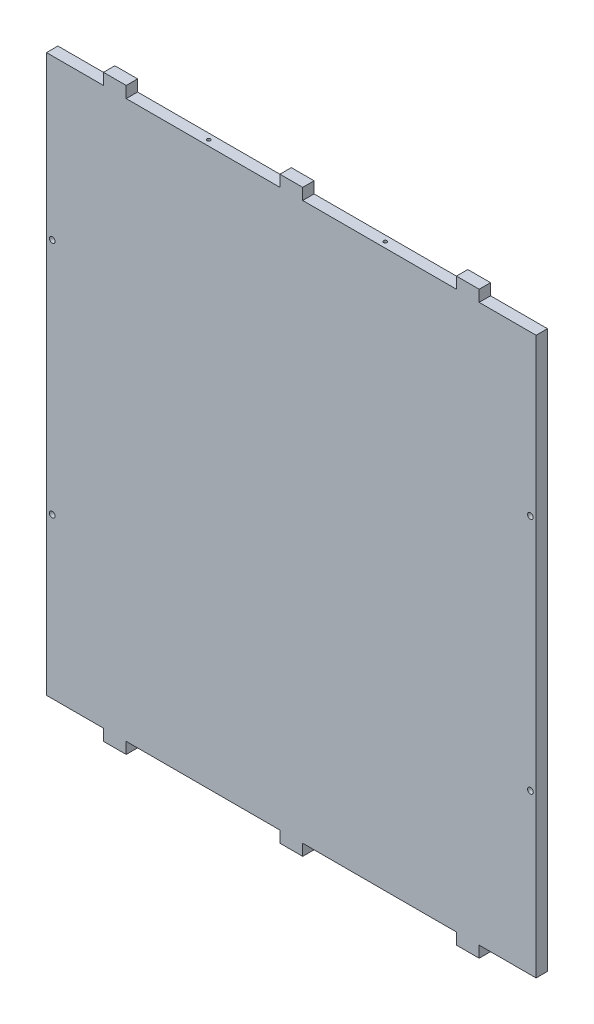
SolidWorks part; units mm, degrees
ref_plane "Ebene vorne" through (0, 0, 0) normal (0, 0, 1) x (1, 0, 0)
ref_plane "Ebene oben" through (0, 0, 0) normal (0, 1, 0) x (1, 0, 0)
ref_plane "Ebene rechts" through (0, 0, 0) normal (1, 0, 0) x (0, 0, -1)
sketch "Skizze1" plane through (0, 0, 0) normal (0, 0, 1) x (1, 0, 0)
  line L0 (0, 0) -> (0, -83406.5938) construction
  line L1 (0, 0) -> (83406.5938, 0) construction
  line L2 (55, 67.225) -> (75, 67.225)
  line L3 (-100, -67.225) -> (100, -67.225)
  line L4 (10.5, -37.555) -> (10.5, -42.555)
  line L5 (-100, 67.225) -> (-85, 67.225)
  line L6 (50.5, -37.555) -> (55.5, -37.555)
  line L7 (-100, -67.225) -> (100, 67.225) construction
  line L8 (-100, 67.225) -> (100, -67.225) construction
  line L9 (100, 47.225) -> (100, 67.225)
  line L10 (75, 67.225) -> (75, 72.225)
  line L11 (75, 72.225) -> (85, 72.225)
  line L12 (85, 67.225) -> (85, 72.225)
  line L13 (85, 67.225) -> (100, 67.225)
  line L14 (45, 67.225) -> (45, 72.225)
  line L15 (45, 72.225) -> (55, 72.225)
  line L16 (55, 67.225) -> (55, 72.225)
  line L17 (50.5, -37.555) -> (50.5, -42.555)
  line L18 (50.5, -42.555) -> (55.5, -42.555)
  line L19 (55.5, -37.555) -> (55.5, -42.555)
  line L20 (15.5, -42.555) -> (10.5, -42.555)
  line L21 (100, 47.225) -> (105, 47.225)
  line L22 (15.5, -37.555) -> (15.5, -42.555)
  line L23 (100, 37.225) -> (105, 37.225)
  line L24 (105, 47.225) -> (105, 37.225)
  line L25 (15.5, -37.555) -> (10.5, -37.555)
  line L26 (-75, 67.225) -> (45, 67.225)
  line L27 (100, -47.225) -> (100, -67.225)
  line L29 (-75, 67.225) -> (-75, 72.225)
  line L30 (-75, 72.225) -> (-85, 72.225)
  line L31 (105, -47.225) -> (105, -37.225)
  line L32 (100, -37.225) -> (105, -37.225)
  line L33 (-85, 67.225) -> (-85, 72.225)
  line L34 (100, -47.225) -> (105, -47.225)
  line L38 (100, 37.225) -> (100, -37.225)
  line L44 (-100, 37.225) -> (-100, -37.225)
  line L48 (-100, -47.225) -> (-105, -47.225)
  line L50 (-100, -37.225) -> (-105, -37.225)
  line L51 (-105, -47.225) -> (-105, -37.225)
  line L53 (-100, -47.225) -> (-100, -67.225)
  line L55 (-105, 47.225) -> (-105, 37.225)
  line L56 (-100, 37.225) -> (-105, 37.225)
  line L58 (-100, 47.225) -> (-105, 47.225)
  line L62 (-100, 47.225) -> (-100, 67.225)
  line L63 (33, -37.555) -> (33, -42.555) construction
  line L64 (25.5, -37.555) -> (40.5, -37.555)
  line L65 (25.5, -37.555) -> (25.5, -42.555)
  line L66 (25.5, -42.555) -> (40.5, -42.555)
  line L67 (40.5, -37.555) -> (40.5, -42.555)
  line L68 (105, 0) -> (105, -50000) construction
  point P5 (0, 0)
  dimension "D1" = 134.45
  dimension "D2" = 200
  dimension "D3" = 10
  dimension "D4" = 20
  dimension "D5" = 5
  dimension "D6" = 20
  dimension "D7" = 20
  dimension "D8" = 29.67
  dimension "D9" = 72
  dimension "D10" = 15
  dimension "D11" = 105
  dimension "D12" = 10
  dimension "D13" = 5
  dimension "D14" = 15
extrude "Aufsatz-Linear austragen1" add sketch "Skizze1" along normal blind 5
sketch "Skizze2" plane through (0, 0, 5) normal (0, 0, 1) x (1, 0, 0)
  line L0 (-42, 48.7841) -> (-42, -49951.2159) construction
  line L1 (-80.5107, -3.925) -> (49919.4893, -3.925) construction
  line L2 (-100, 67.225) -> (-85, 67.225) construction
  line L4 (100, 37.225) -> (100, -37.225) construction
  circle A0 centre (-59.5, 4.075) radius 2.75
  circle A1 centre (-24.5, 4.075) radius 2.75 construction
  circle A2 centre (-59.5, -11.925) radius 2.75 construction
  circle A3 centre (-24.5, -11.925) radius 2.75
  dimension "D1" = 5.5
  dimension "D2" = 63.15
  dimension "D3" = 142
  dimension "D4" = 35
  dimension "D5" = 16
extrude "Schnitt-Linear austragen1" cut sketch "Skizze2" against normal through all
sketch "Skizze3" plane through (0, 0, 5) normal (0, 0, 1) x (1, 0, 0)
  line L0 (33, -42.555) -> (33, -17.555) construction
  line L1 (25, -17.555) -> (41, -17.555)
  line L2 (23, -19.555) -> (23, -35.555)
  line L3 (37, -37.555) -> (41, -37.555)
  line L4 (43, -19.555) -> (43, -35.555)
  line L5 (-14.5, -32.225) -> (4.5, -32.225) construction
  line L6 (-17.5, -35.225) -> (-17.5, -54.225) construction
  line L7 (-14.5, -57.225) -> (4.5, -57.225) construction
  line L8 (7.5, -35.225) -> (7.5, -54.225) construction
  line L9 (25.5, -42.555) -> (40.5, -42.555) construction
  line L10 (25.5, -37.555) -> (40.5, -37.555) construction
  line L11 (29, -37.555) -> (25, -37.555)
  line L12 (-66.5, 54.225) -> (-66.5, 35.225)
  line L13 (37, -37.555) -> (29, -37.555)
  line L14 (-5, -32.225) -> (-5, -50032.225) construction
  line L17 (-88.5, 32.225) -> (-69.5, 32.225)
  line L18 (-100, -67.225) -> (100, -67.225) construction
  line L19 (-5, 57.225) -> (49995, 57.225) construction
  line L20 (-100, 67.225) -> (-85, 67.225) construction
  line L21 (-42, 57.225) -> (-42, -49942.775) construction
  line L24 (4.5, 57.225) -> (-14.5, 57.225)
  line L25 (7.5, 54.225) -> (7.5, 35.225)
  line L26 (4.5, 32.225) -> (-14.5, 32.225)
  line L27 (-17.5, 54.225) -> (-17.5, 35.225)
  line L28 (-91.5, 54.225) -> (-91.5, 35.225)
  line L29 (-88.5, 57.225) -> (-69.5, 57.225)
  line L30 (-79, 57.225) -> (-79, -49942.775) construction
  line L31 (-5, 22.3625) -> (49995, 22.3625) construction
  line L32 (4.5, -12.5) -> (-14.5, -12.5) construction
  line L33 (-17.5, -9.5) -> (-17.5, 9.5) construction
  line L34 (4.5, 12.5) -> (-14.5, 12.5) construction
  line L35 (7.5, -9.5) -> (7.5, 9.5) construction
  line L36 (4.5, 32.225) -> (4.5, 12.5) construction
  line L37 (4.5, -12.5) -> (4.5, -32.225) construction
  line L38 (4.5, -32.225) -> (4.5, -12.5) construction
  circle A0 centre (-24.5, -11.925) radius 2.75 construction
  arc A1 (23, -35.555) -> (25, -37.555) centre (25, -35.555) ccw
  arc A2 (43, -35.555) -> (41, -37.555) centre (41, -35.555) cw
  arc A3 (43, -19.555) -> (41, -17.555) centre (41, -19.555) ccw
  arc A4 (25, -17.555) -> (23, -19.555) centre (25, -19.555) ccw
  arc A5 (-17.5, -54.225) -> (-14.5, -57.225) centre (-14.5, -54.225) ccw construction
  arc A6 (7.5, -54.225) -> (4.5, -57.225) centre (4.5, -54.225) cw construction
  arc A8 (7.5, -35.225) -> (4.5, -32.225) centre (4.5, -35.225) ccw construction
  arc A9 (-14.5, -32.225) -> (-17.5, -35.225) centre (-14.5, -35.225) ccw construction
  arc A10 (7.5, 35.225) -> (4.5, 32.225) centre (4.5, 35.225) cw
  arc A11 (-14.5, 32.225) -> (-17.5, 35.225) centre (-14.5, 35.225) cw
  arc A12 (-17.5, 54.225) -> (-14.5, 57.225) centre (-14.5, 54.225) cw
  arc A14 (4.5, 57.225) -> (7.5, 54.225) centre (4.5, 54.225) cw
  arc A15 (-88.5, 57.225) -> (-91.5, 54.225) centre (-88.5, 54.225) ccw
  arc A16 (-66.5, 54.225) -> (-69.5, 57.225) centre (-69.5, 54.225) ccw
  arc A17 (-69.5, 32.225) -> (-66.5, 35.225) centre (-69.5, 35.225) ccw
  arc A18 (-91.5, 35.225) -> (-88.5, 32.225) centre (-88.5, 35.225) ccw
  circle A19 centre (-59.5, 4.075) radius 2.75 construction
  arc A20 (-17.5, -9.5) -> (-14.5, -12.5) centre (-14.5, -9.5) ccw construction
  arc A21 (-14.5, 12.5) -> (-17.5, 9.5) centre (-14.5, 9.5) ccw construction
  arc A22 (7.5, 9.5) -> (4.5, 12.5) centre (4.5, 9.5) ccw construction
  arc A23 (4.5, -12.5) -> (7.5, -9.5) centre (4.5, -9.5) ccw construction
  point P19 (23, -37.555)
  point P22 (43, -37.555)
  point P25 (43, -17.555)
  point P28 (23, -17.555)
  point P52 (43, -37.555)
  point P53 (-5, -32.225)
  point P67 (-17.5, 32.225)
  point P70 (-17.5, 57.225)
  point P73 (7.5, 57.225)
  point P86 (-91.5, 57.225)
  point P87 (-66.5, 57.225)
  point P88 (-66.5, 32.225)
  point P91 (-79, 57.225)
  dimension "D1" = 20
  dimension "D2" = 20
  dimension "D6" = 25
  dimension "D3" = 2
  dimension "D7" = 3
  dimension "D12" = 25
  dimension "D5" = 19.5
  dimension "D15" = 2
  dimension "D17" = 3
  dimension "D18" = 19.5
  dimension "D4" = 10
  dimension "D8" = 25
  dimension "D9" = 25
  dimension "D11" = 10
  dimension "D13" = 0
  dimension "D14" = 8
extrude "Schnitt-Linear austragen2" cut sketch "Skizze3" against normal through all
sketch "Skizze4" plane through (0, 0, 5) normal (0, 0, 1) x (1, 0, 0)
  line L0 (55, 67.225) -> (75, 67.225) construction
  line L1 (100, 47.225) -> (100, 67.225) construction
  line L2 (-100, -67.225) -> (100, -67.225) construction
  line L3 (-80.5, -30.925) -> (49919.5, -30.925) construction
  line L4 (-80.5, -30.925) -> (-80.5, -50030.925) construction
  circle A0 centre (45.5, 53.325) radius 7.5 construction
  circle A1 centre (-80.5, -30.925) radius 7.5
  circle A2 centre (-59.5, 4.075) radius 2.75 construction
  circle A3 centre (-80.5, -11.925) radius 7.5
  circle A4 centre (-80.5, -49.925) radius 7.5
  dimension "D1" = 13.9
  dimension "D3" = 15
  dimension "D5" = 21
  dimension "D6" = 19
  dimension "D2" = 54.5
  dimension "D4" = 36.3
extrude "Schnitt-Linear austragen3" cut sketch "Skizze4" against normal through all
sketch "Skizze5" plane through (0, 0, 5) normal (0, 0, 1) x (1, 0, 0)
  line L0 (-8, -45.225) -> (-8, -3.225) construction
  line L1 (83, -12.225) -> (-8, -12.225) construction
  line L2 (-100, -67.225) -> (100, -67.225) construction
  line L3 (100, 37.225) -> (100, -37.225) construction
  line L4 (-30.2483, -49.225) -> (49969.7517, -49.225) construction
  line L5 (-17.9531, -56.225) -> (49982.0469, -56.225) construction
  line L6 (22.5, -56.9878) -> (22.5, -50056.9878) construction
  line L7 (37.5, -10.225) -> (37.5, -50010.225) construction
  circle A0 centre (-8, -45.225) radius 0.75
  circle A1 centre (-8, -3.225) radius 0.75
  circle A2 centre (83, -12.225) radius 0.75
  circle A3 centre (-15, -56.225) radius 6
  circle A4 centre (0, -56.225) radius 6
  circle A5 centre (15, -56.225) radius 6
  circle A6 centre (30, -56.225) radius 6
  circle A7 centre (45, -56.225) radius 6
  circle A8 centre (60, -56.225) radius 6
  circle A9 centre (75, -56.225) radius 6
  circle A10 centre (90, -56.225) radius 6
  point P36 (37.5, -12.225)
  dimension "D1" = 1.5
  dimension "D9" = 12
  dimension "D2" = 42
  dimension "D4" = 91
  dimension "D3" = 9
  dimension "D5" = 22
  dimension "D6" = 17
  dimension "D7" = 4
  dimension "D10" = 7
  dimension "D11" = 15
  dimension "D8" = 8
extrude "Sensors" cut sketch "Skizze5" against normal through all
sketch "Skizze6" plane through (0, 0, 0) normal (0, 0, -1) x (-1, 0, 0)
  line L0 (100, -67.225) -> (-100, -67.225) construction
  line L1 (160, 47.225) -> (160, 37.225)
  line L2 (100, 67.225) -> (100, -67.225)
  line L3 (100, -67.225) -> (160, -67.225)
  line L4 (160, 67.225) -> (160, 47.225)
  line L6 (100, -37.225) -> (105, -37.225) construction
  line L7 (160, -47.225) -> (160, -67.225)
  line L8 (100, -47.225) -> (105, -47.225) construction
  line L9 (100, 47.225) -> (105, 47.225) construction
  line L10 (100, 37.225) -> (105, 37.225) construction
  line L11 (75, 67.225) -> (-45, 67.225) construction
  line L17 (160, 37.225) -> (160, -37.225)
  line L18 (-30.5, 67.225) -> (100, 67.225)
  line L19 (-30.5, 67.225) -> (-30.5, 177.225)
  line L20 (-30.5, 177.225) -> (160, 177.225)
  line L21 (160, 67.225) -> (160, 177.225)
  line L22 (-100, 47.225) -> (-100, 67.225) construction
  line L23 (160, -37.225) -> (160, -47.225)
  dimension "D1" = 60
  dimension "D2" = 110
  dimension "D3" = 69.5
extrude "Aufsatz-Linear austragen2" add sketch "Skizze6" against normal blind 5
sketch "Skizze7" plane through (0, 0, 0) normal (0, 0, -1) x (-1, 0, 0)
  line L0 (71.5, 32.775) -> (96.5, 32.775) construction
  line L1 (160, -67.225) -> (-100, -67.225) construction
  line L4 (91.5, 54.225) -> (91.5, 35.225) construction
  line L5 (46.5, 32.775) -> (71.5, 32.775) construction
  line L6 (122.7956, 60.525) -> (50122.7956, 60.525) construction
  circle A0 centre (71.5, 32.775) radius 1.25
  circle A1 centre (96.5, 32.775) radius 1.25
  circle A4 centre (46.5, 32.775) radius 1.25
  dimension "D3" = 2.5
  dimension "D1" = 100
  dimension "D2" = 25
  dimension "D4" = 20
extrude "Schnitt-Linear austragen5" cut sketch "Skizze7" against normal through all
sketch "Sketch1" plane through (0, 0, 5) normal (0, 0, 1) x (1, 0, 0)
  line L1 (30.5, 177.225) -> (100, 177.225)
  line L2 (30.5, 177.225) -> (30.5, 67.225)
  line L3 (30.5, 67.225) -> (100, 67.225)
  line L4 (100, 177.225) -> (100, 67.225)
extrude "Boss-Extrude1" add sketch "Sketch1" against normal blind 5
sketch "Skizze9" plane through (0, 0, 5) normal (0, 0, 1) x (1, 0, 0)
  line L0 (-33.1526, 41.015) -> (49966.8474, 41.015) construction
  line L1 (38.5, 36.3664) -> (38.5, 48631.464) construction
  line L5 (-2, 7.1234) -> (-2, 89.5656) construction
  line L7 (-17.5, 54.225) -> (-17.5, 35.225) construction
  line L8 (4.5, 57.225) -> (-14.5, 57.225) construction
  circle A0 centre (8, 71.515) radius 0.75
  circle A1 centre (69, 71.515) radius 0.75
  circle A2 centre (8, 10.515) radius 0.75
  circle A3 centre (69, 10.515) radius 0.75
  circle A4 centre (-2, 5.015) radius 6
  circle A5 centre (-2, 29.015) radius 6
  circle A6 centre (-2, 53.015) radius 6
  circle A7 centre (-2, 77.015) radius 6
  dimension "D1" = 1.5
  dimension "D8" = 12
  dimension "D2" = 61
  dimension "D3" = 61
  dimension "D7" = 24
  dimension "D5" = 15.5
  dimension "D9" = 4.21
  dimension "D4" = 10
  dimension "D6" = 4
extrude "DiscreteChannel" cut sketch "Skizze9" against normal through all
sketch "Skizze10" plane through (0, 0, 5) normal (0, 0, 1) x (1, 0, 0)
  line L0 (-50, 127.2474) -> (-50, -49872.7526) construction
  line L1 (-69.94, 115.225) -> (49930.06, 115.225) construction
  line L4 (-50.8687, 166.225) -> (49949.1313, 166.225) construction
  line L5 (-75.5, 136.225) -> (49924.5, 136.225) construction
  line L6 (-72.5, 172.225) -> (-27.5, 172.225) construction
  line L7 (-72.5, 166.225) -> (-72.5, 151.225) construction
  line L8 (-160, 177.225) -> (100, 177.225) construction
  line L9 (100, 47.225) -> (100, 177.225) construction
  circle A0 centre (-4, 136.225) radius 0.75
  circle A1 centre (-4, 94.225) radius 0.75
  circle A2 centre (-96, 136.225) radius 0.75
  circle A3 centre (-96, 94.225) radius 0.75
  circle A4 centre (-72.5, 166.225) radius 6
  circle A5 centre (-2, 5.015) radius 6 construction
  circle A6 centre (-57.5, 166.225) radius 6
  circle A7 centre (-42.5, 166.225) radius 6
  circle A8 centre (-27.5, 166.225) radius 6
  circle A9 centre (-27.5, 151.225) radius 6
  circle A10 centre (-42.5, 151.225) radius 6
  circle A11 centre (-57.5, 151.225) radius 6
  circle A12 centre (-72.5, 151.225) radius 6
  point P20 (-50, 172.225)
  dimension "D6" = 4
  dimension "D5" = 1.5
  dimension "D1" = 42
  dimension "D2" = 92
  dimension "D7" = 15
  dimension "D9" = 30
  dimension "D8" = 15
  dimension "D4" = 11
  dimension "D10" = 150
  dimension "D3" = 2
extrude "ContChannel" cut sketch "Skizze10" against normal through all
sketch "Sketch2" plane through (0, 0, 5) normal (0, 0, 1) x (1, 0, 0)
  line L0 (-14.5, 32.225) -> (-7.0691, 32.225) construction
  line L1 (3.0691, 32.225) -> (4.5, 32.225) construction
  line L2 (7.5, 35.225) -> (7.5, 54.225) construction
  line L3 (4.5, 57.225) -> (2.275, 57.225) construction
  line L4 (-6.275, 57.225) -> (-14.5, 57.225) construction
  line L5 (-17.5, 54.225) -> (-17.5, 35.225) construction
  line L6 (-14.5, 32.225) -> (-7.0691, 32.225)
  line L7 (3.0691, 32.225) -> (4.5, 32.225)
  line L8 (7.5, 35.225) -> (7.5, 54.225)
  line L9 (4.5, 57.225) -> (2.275, 57.225)
  line L10 (-6.275, 57.225) -> (-14.5, 57.225)
  line L11 (-17.5, 54.225) -> (-17.5, 35.225)
  arc A0 (-17.5, 35.225) -> (-14.5, 32.225) centre (-14.5, 35.225) ccw construction
  arc A1 (-7.0691, 32.225) -> (3.0691, 32.225) centre (-2, 29.015) ccw construction
  arc A2 (4.5, 32.225) -> (7.5, 35.225) centre (4.5, 35.225) ccw construction
  arc A3 (7.5, 54.225) -> (4.5, 57.225) centre (4.5, 54.225) ccw construction
  arc A4 (2.275, 57.225) -> (-6.275, 57.225) centre (-2, 53.015) ccw construction
  arc A5 (-14.5, 57.225) -> (-17.5, 54.225) centre (-14.5, 54.225) ccw construction
  arc A6 (-17.5, 35.225) -> (-14.5, 32.225) centre (-14.5, 35.225) ccw
  arc A7 (-7.0691, 32.225) -> (3.0691, 32.225) centre (-2, 29.015) ccw construction
  arc A8 (4.5, 32.225) -> (7.5, 35.225) centre (4.5, 35.225) ccw
  arc A9 (7.5, 54.225) -> (4.5, 57.225) centre (4.5, 54.225) ccw
  arc A10 (2.275, 57.225) -> (-6.275, 57.225) centre (-2, 53.015) ccw construction
  arc A11 (-14.5, 57.225) -> (-17.5, 54.225) centre (-14.5, 54.225) ccw
  arc A12 (-7.0691, 32.225) -> (3.0691, 32.225) centre (-2, 29.015) cw
  arc A13 (-6.275, 57.225) -> (2.275, 57.225) centre (-2, 53.015) ccw
extrude "Boss-Extrude2" add sketch "Sketch2" against normal blind 5
sketch "Skizze8" plane through (0, 0, 5) normal (0, 0, 1) x (1, 0, 0)
  line L0 (-165.5788, 126.725) -> (49834.4212, 126.725) construction
  line L1 (78, 176.1292) -> (78, 50176.1292) construction
  line L2 (-160, 177.225) -> (100, 177.225) construction
  line L3 (100, 47.225) -> (100, 177.225) construction
  line L5 (62.5, 100.225) -> (93.5, 100.225) construction
  circle A0 centre (62.5, 153.225) radius 0.75
  circle A1 centre (93.5, 153.225) radius 0.75
  circle A2 centre (62.5, 100.225) radius 0.75
  circle A3 centre (93.5, 100.225) radius 0.75
  circle A4 centre (78, 86.225) radius 7.5
  circle A5 centre (-80.5, -11.925) radius 7.5 construction
  circle A6 centre (78, 167.225) radius 7.5
  dimension "D1" = 1.5
  dimension "D2" = 53
  dimension "D3" = 31
  dimension "D4" = 14
  dimension "D5" = 10
  dimension "D6" = 6.5
extrude "StepDownConverter" cut sketch "Skizze8" against normal through all
sketch "Sketch3" plane through (0, 0, 5) normal (0, 0, 1) x (1, 0, 0)
  line L0 (46.6666, 126.725) -> (50046.6666, 126.725) construction
  line L1 (100, 47.225) -> (100, 177.225) construction
  line L2 (93.5, 153.225) -> (93.5, 100.225) construction
  line L3 (78, 167.225) -> (50078, 167.225) construction
  circle A0 centre (21.85, 147.68) radius 0.75
  circle A1 centre (87.89, 102.59) radius 0.75
  circle A2 centre (87.89, 150.86) radius 0.75
  circle A3 centre (21.85, 105.77) radius 0.75
  circle A4 centre (13, 167.225) radius 5
  circle A5 centre (28, 167.225) radius 5
  circle A6 centre (43, 167.225) radius 5
  circle A7 centre (58, 167.225) radius 5
  circle A8 centre (78, 167.225) radius 7.5 construction
  circle A9 centre (13, 86.225) radius 5
  point P10 (93.5, 126.725)
  dimension "D4" = 1.5
  dimension "D6" = 10
  dimension "D1" = 66.04
  dimension "D2" = 41.91
  dimension "D3" = 3.18
  dimension "D5" = 12.11
  dimension "D8" = 15
  dimension "D9" = 20
  dimension "D7" = 4
extrude "BBB" cut sketch "Sketch3" against normal blind 5
sketch "Sketch4" plane through (0, 0, 5) normal (0, 0, 1) x (1, 0, 0)
  line L0 (-88.5, 32.225) -> (-72.6225, 32.225) construction
  line L1 (-70.3775, 32.225) -> (-69.5, 32.225) construction
  line L2 (-66.5, 35.225) -> (-66.5, 54.225) construction
  line L3 (-69.5, 57.225) -> (-88.5, 57.225) construction
  line L4 (-91.5, 54.225) -> (-91.5, 35.225) construction
  line L5 (-88.5, 32.225) -> (-72.6225, 32.225)
  line L6 (-70.3775, 32.225) -> (-69.5, 32.225)
  line L7 (-66.5, 35.225) -> (-66.5, 54.225)
  line L8 (-69.5, 57.225) -> (-88.5, 57.225)
  line L9 (-91.5, 54.225) -> (-91.5, 35.225)
  arc A0 (-91.5, 35.225) -> (-88.5, 32.225) centre (-88.5, 35.225) ccw construction
  arc A1 (-72.6225, 32.225) -> (-70.3775, 32.225) centre (-71.5, 32.775) ccw construction
  arc A2 (-69.5, 32.225) -> (-66.5, 35.225) centre (-69.5, 35.225) ccw construction
  arc A3 (-66.5, 54.225) -> (-69.5, 57.225) centre (-69.5, 54.225) ccw construction
  arc A4 (-88.5, 57.225) -> (-91.5, 54.225) centre (-88.5, 54.225) ccw construction
  arc A5 (-91.5, 35.225) -> (-88.5, 32.225) centre (-88.5, 35.225) ccw
  arc A6 (-72.6225, 32.225) -> (-70.3775, 32.225) centre (-71.5, 32.775) ccw construction
  arc A7 (-69.5, 32.225) -> (-66.5, 35.225) centre (-69.5, 35.225) ccw
  arc A8 (-66.5, 54.225) -> (-69.5, 57.225) centre (-69.5, 54.225) ccw
  arc A9 (-88.5, 57.225) -> (-91.5, 54.225) centre (-88.5, 54.225) ccw
  arc A10 (-72.6225, 32.225) -> (-70.3775, 32.225) centre (-71.5, 32.775) cw
extrude "Boss-Extrude3" add sketch "Sketch4" against normal blind 5
sketch "Sketch5" plane through (0, 0, 5) normal (0, 0, 1) x (1, 0, 0)
  line L0 (-160, -67.225) -> (100, -67.225) construction
  line L1 (-160, 177.225) -> (-105, 177.225)
  line L2 (-160, 177.225) -> (-160, -67.225)
  line L3 (-160, -67.225) -> (-105, -67.225)
  line L4 (-105, 177.225) -> (-105, -67.225)
  line L5 (100, 47.225) -> (100, 177.225) construction
  dimension "D1" = 205
extrude "Cut-Extrude2" cut sketch "Sketch5" against normal blind 5
sketch "Sketch6" plane through (0, 0, 5) normal (0, 0, 1) x (1, 0, 0)
  line L0 (-105, 82.775) -> (49895, 82.775) construction
  line L2 (-105, -67.225) -> (-105, 177.225) construction
  line L3 (-95, 82.775) -> (-95, -49917.225) construction
  circle A0 centre (-96.5, 32.775) radius 1.25 construction
  circle A1 centre (-95, 82.775) radius 5
  circle A2 centre (-80, 82.775) radius 5
  circle A3 centre (-95, -32.225) radius 5
  circle A4 centre (-65, 82.775) radius 5
  dimension "D2" = 10
  dimension "D1" = 50
  dimension "D4" = 10
  dimension "D5" = 15
  dimension "D6" = 115
  dimension "D3" = 3
extrude "Cut-Extrude3" cut sketch "Sketch6" against normal blind 5
sketch "Sketch7" plane through (0, 0, 5) normal (0, 0, 1) x (1, 0, 0)
  line L0 (100, 47.225) -> (100, 177.225) construction
  line L1 (100, 157.225) -> (105, 157.225)
  line L2 (100, 157.225) -> (100, 147.225)
  line L3 (100, 147.225) -> (105, 147.225)
  line L4 (105, 157.225) -> (105, 147.225)
  line L5 (100, -37.225) -> (105, -37.225) construction
  line L6 (-105, 177.225) -> (100, 177.225) construction
  dimension "D1" = 10
  dimension "D2" = 20
extrude "Boss-Extrude4" add sketch "Sketch7" against normal blind 5
sketch "Sketch8" plane through (0, 0, 5) normal (0, 0, 1) x (1, 0, 0)
  line L0 (-105, -67.225) -> (100, -67.225) construction
  line L1 (-85, -67.225) -> (-75, -67.225)
  line L2 (-85, -67.225) -> (-85, -72.225)
  line L3 (-85, -72.225) -> (-75, -72.225)
  line L4 (-75, -67.225) -> (-75, -72.225)
  line L5 (-75, -67.225) -> (70, -67.225) construction
  line L6 (-7.5, -67.225) -> (2.5, -67.225)
  line L7 (-7.5, -67.225) -> (-7.5, -72.225)
  line L8 (-7.5, -72.225) -> (2.5, -72.225)
  line L9 (2.5, -67.225) -> (2.5, -72.225)
  line L10 (70, -67.225) -> (80, -67.225)
  line L11 (70, -67.225) -> (70, -72.225)
  line L12 (70, -72.225) -> (80, -72.225)
  line L13 (80, -67.225) -> (80, -72.225)
  line L14 (-2.5, -67.225) -> (-2.5, -106.7893) construction
  line L15 (-105, -67.225) -> (-105, 177.225) construction
  line L16 (100, -47.225) -> (100, -67.225) construction
  line L17 (-105, 55) -> (49895, 55) construction
  line L18 (70, 182.225) -> (80, 182.225)
  line L19 (80, 177.225) -> (80, 182.225)
  line L20 (70, 177.225) -> (80, 177.225)
  line L21 (70, 177.225) -> (70, 182.225)
  line L22 (-7.5, 182.225) -> (2.5, 182.225)
  line L23 (-7.5, 177.225) -> (2.5, 177.225)
  line L24 (-7.5, 177.225) -> (-7.5, 182.225)
  line L25 (-85, 177.225) -> (-75, 177.225)
  line L26 (-75, 177.225) -> (-75, 182.225)
  line L27 (-85, 182.225) -> (-75, 182.225)
  line L28 (-85, 177.225) -> (-85, 182.225)
  line L29 (2.5, 177.225) -> (2.5, 182.225)
  point P22 (-105, 55)
  dimension "D1" = 5
  dimension "D2" = 10
  dimension "D3" = 20
  dimension "D4" = 20
extrude "Boss-Extrude5" add sketch "Sketch8" against normal blind 5
sketch "Sketch9" plane through (0, 0, 0) normal (0, 0, -1) x (-1, 0, 0)
  line L0 (-80, -67.225) -> (-100, -67.225) construction
  line L1 (105, 177.225) -> (-105, 177.225)
  line L2 (105, 177.225) -> (105, -67.225)
  line L3 (105, -67.225) -> (-105, -67.225)
  line L4 (-105, 177.225) -> (-105, -67.225)
  line L5 (-105, -47.225) -> (-105, -37.225) construction
  circle A0 centre (59.5, 4.075) radius 2.75 construction
  circle A1 centre (24.5, -11.925) radius 2.75 construction
  circle A2 centre (59.5, 4.075) radius 2.75
  circle A3 centre (24.5, -11.925) radius 2.75
  circle A4 centre (80.5, -49.925) radius 7.5 construction
  circle A5 centre (80.5, -30.925) radius 7.5 construction
  circle A6 centre (80.5, -11.925) radius 7.5 construction
  circle A7 centre (80.5, -49.925) radius 7.5
  circle A8 centre (80.5, -30.925) radius 7.5
  circle A9 centre (80.5, -11.925) radius 7.5
extrude "Boss-Extrude6" add sketch "Sketch9" against normal blind 5
sketch "Sketch10" plane through (0, 0, 0) normal (0, 0, -1) x (-1, 0, 0)
  line L0 (-61.136, 82.225) -> (49938.864, 82.225) construction
  line L1 (-105, 177.225) -> (-105, -67.225) construction
  line L2 (-80, 177.225) -> (-105, 177.225) construction
  circle A0 centre (-45, 82.225) radius 1.25
  circle A1 centre (-20, 82.225) radius 1.25
  circle A2 centre (5, 82.225) radius 1.25
  dimension "D2" = 2.5
  dimension "D3" = 25
  dimension "D4" = 60
  dimension "D5" = 95
  dimension "D1" = 3
extrude "Cut-Extrude4" cut sketch "Sketch10" against normal blind 5
sketch "Sketch11" plane through (0, 0, 0) normal (0, 0, -1) x (-1, 0, 0)
  line L0 (0, 182.225) -> (0, -49817.775) construction
  line L2 (-102.5, 177.225) -> (-102.5, -49822.775) construction
  line L4 (105, 55) -> (50105, 55) construction
  line L5 (105, -67.225) -> (105, 177.225) construction
  line L6 (-105, 177.225) -> (-105, -67.225) construction
  line L7 (-80, 177.225) -> (-105, 177.225) construction
  circle A0 centre (-102.5, 107.225) radius 1.25
  circle A1 centre (-102.5, 2.775) radius 1.25
  circle A2 centre (102.5, 2.775) radius 1.25
  circle A3 centre (102.5, 107.225) radius 1.25
  point P13 (105, 55)
  dimension "D2" = 2.5
  dimension "D3" = 70
  dimension "D1" = 2.5
  dimension "D4" = 2.5
extrude "Cut-Extrude5" cut sketch "Sketch11" against normal through all
sketch "Sketch12" plane through (0, 177.225, 0) normal (0, 1, 0) x (1, 0, 0)
  line L0 (70, -2.5) -> (2.5, -2.5) construction
  line L1 (70, 0) -> (70, -5) construction
  line L2 (2.5, 0) -> (2.5, -5) construction
  line L3 (2.5, -2.5) -> (-7.5, -2.5) construction
  line L4 (-7.5, 0) -> (-7.5, -5) construction
  line L5 (-7.5, -2.5) -> (-75, -2.5) construction
  line L6 (-75, 0) -> (-75, -5) construction
  circle A0 centre (-41.25, -2.5) radius 0.75
  circle A1 centre (36.25, -2.5) radius 0.75
  dimension "D1" = 1.5
extrude "Cut-Extrude6" cut sketch "Sketch12" against normal blind 10
ref_plane "Plane1" through (0, 55, 0) normal (0, 1, 0) x (1, 0, 0)
mirror "Mirror1" about plane through (0, 55, 0) normal (0, 1, 0) of "Cut-Extrude6"
sketch "Sketch13" plane through (0, 0, 0) normal (0, 0, -1) x (-1, 0, 0)
  line L1 (-52.0709, 89.4) -> (14.8124, 89.4)
  line L2 (-52.0709, 89.4) -> (-52.0709, 70.3932)
  line L3 (-52.0709, 70.3932) -> (14.8124, 70.3932)
  line L4 (14.8124, 89.4) -> (14.8124, 70.3932)
  line L5 (96.0029, 36.221) -> (67.6882, 36.221)
  line L6 (96.0029, 36.221) -> (96.0029, -64.3848)
  line L7 (96.0029, -64.3848) -> (67.6882, -64.3848)
  line L8 (67.6882, 36.221) -> (67.6882, -64.3848)
  line L9 (62.766, 9.5126) -> (18.4675, 9.5126)
  line L10 (62.766, 9.5126) -> (62.766, -19.6934)
  line L11 (62.766, -19.6934) -> (18.4675, -19.6934)
  line L12 (18.4675, 9.5126) -> (18.4675, -19.6934)
extrude "Boss-Extrude7" add sketch "Sketch13" against normal up to surface (5 mm away) up to face at (-101.25, 107.225, 5)
sketch "Sketch14" plane through (-105, 0, 0) normal (-1, 0, 0) x (0, 0, 1)
  line L4 (5, -67.225) -> (5, 177.225)
  line L5 (5, 177.225) -> (0, 177.225)
  line L6 (0, 177.225) -> (0, -67.225)
  line L7 (0, -67.225) -> (5, -67.225)
  line L8 (5, -67.225) -> (5, 177.225)
  line L9 (5, 177.225) -> (0, 177.225)
  line L10 (0, 177.225) -> (0, -67.225)
  line L11 (0, -67.225) -> (5, -67.225)
  dimension "D1" = 0
extrude "Boss-Extrude8" add sketch "Sketch14" along normal blind 5
sketch "Sketch15" plane through (0, 0, 0) normal (0, 0, -1) x (-1, 0, 0)
  circle A0 centre (102.5, 2.775) radius 1.25 construction
  circle A1 centre (102.5, 107.225) radius 1.25 construction
  circle A2 centre (102.5, 2.775) radius 1.25
  circle A3 centre (102.5, 107.225) radius 1.25
  circle A4 centre (107.5, 2.775) radius 1.25
  circle A5 centre (107.5, 107.225) radius 1.25
  dimension "D2" = 5
  dimension "D1" = 2
extrude "Cut-Extrude7" cut sketch "Sketch15" against normal blind 5
sketch "Sketch16" plane through (0, 0, 0) normal (0, 0, -1) x (-1, 0, 0)
  circle A0 centre (102.5, 2.775) radius 1.25 construction
  circle A1 centre (102.5, 107.225) radius 1.25 construction
  circle A2 centre (102.5, 2.775) radius 1.25
  circle A3 centre (102.5, 107.225) radius 1.25
extrude "Boss-Extrude9" add sketch "Sketch16" against normal blind 5
equation "\"m3-gewinde\"= 1.5"
equation "\"m3-durchgang\"= 2.5"
equation "\"D1@Skizze5\"=\"m3-gewinde\""
equation "\"stecker-durchgang\"= 12"
equation "\"D9@Skizze5\"=\"stecker-durchgang\""
equation "\"D3@Skizze7\"=\"m3-durchgang\""
equation "\"D1@Skizze8\"=\"m3-gewinde\""
equation "\"D1@Skizze9\"=\"m3-gewinde\""
equation "\"D8@Skizze9\"=\"stecker-durchgang\""
equation "\"D5@Skizze10\"=\"m3-gewinde\""
